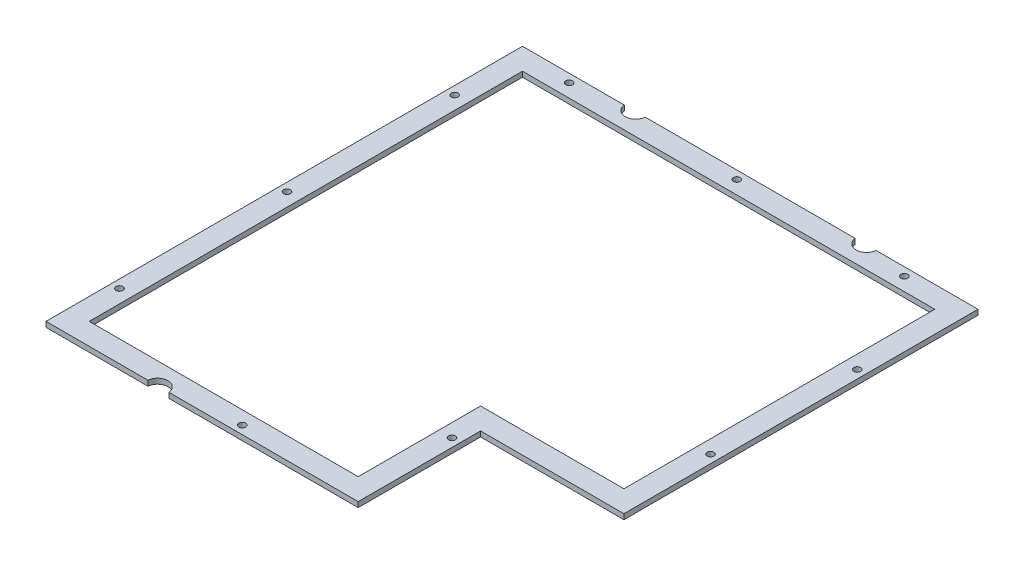
SolidWorks part; units mm, degrees
ref_plane "Front Plane" through (0, 0, 0) normal (0, 0, 1) x (1, 0, 0)
ref_plane "Top Plane" through (0, 0, 0) normal (0, 1, 0) x (1, 0, 0)
ref_plane "Right Plane" through (0, 0, 0) normal (1, 0, 0) x (0, 0, -1)
ref_plane "Plane1" through (0, 0, 0) normal (0, 1, 0) x (1, 0, 0)
sketch "Sketch1" plane through (0, 0, 0) normal (0, 1, 0) x (1, 0, 0)
  line L0 (-138.1125, 144.4625) -> (138.1125, 144.4625)
  line L1 (138.1125, 144.4625) -> (138.1125, -70.2437)
  line L2 (138.1125, -70.2437) -> (51.1937, -70.2437)
  line L3 (51.1937, -70.2437) -> (51.1937, -144.4625)
  line L4 (51.1937, -144.4625) -> (-138.1125, -144.4625)
  line L5 (-138.1125, -144.4625) -> (-138.1125, 144.4625)
  line L6 (-125.0188, 131.3688) -> (125.0188, 131.3688)
  line L7 (125.0188, 131.3688) -> (125.0188, -57.15)
  line L8 (125.0188, -57.15) -> (38.1, -57.15)
  line L9 (38.1, -57.15) -> (38.1, -131.3688)
  line L10 (38.1, -131.3688) -> (-125.0188, -131.3688)
  line L11 (-125.0188, -131.3688) -> (-125.0188, 131.3688)
  line L12 (0, -158.9087) -> (0, 158.9087) construction
  dimension "D1" = 13.0937
  dimension "D2" = 13.0937
  dimension "D3" = 13.0937
  dimension "D4" = 13.0937
  dimension "D5" = 13.0937
  dimension "D6" = 250.0376
  dimension "D7" = 262.7376
  dimension "D8" = 163.1188
  dimension "D9" = 188.5188
extrude "Extrude1" add sketch "Sketch1" along normal blind 3.175
sketch "Sketch2" plane through (0, 3.175, 0) normal (0, 1, 0) x (-1, 0, 0)
  line L0 (0, -158.9087) -> (0, 158.9087) construction
  circle A0 centre (24.13, 139.446) radius 2.0701
  circle A1 centre (104.775, -139.446) radius 2.0701
  circle A2 centre (3.175, -139.446) radius 2.0701
  circle A3 centre (133.096, 104.9366) radius 2.0701
  circle A4 centre (133.096, 3.3366) radius 2.0701
  circle A5 centre (133.096, -98.2634) radius 2.0701
  circle A6 centre (-98.425, -139.446) radius 2.0701
  circle A7 centre (-133.096, -76.2) radius 2.0701
  circle A8 centre (-133.096, 12.7) radius 2.0701
  circle A9 centre (-46.1772, 82.55) radius 2.0701
  point P20 (138.1125, 0)
  point P21 (-138.1125, 0)
  point P22 (0, 144.4625)
  point P23 (0, -144.4625)
extrude "Extrude2" cut sketch "Sketch2" against normal through all
sketch "Sketch3" plane through (0, 3.175, 0) normal (0, 1, 0) x (-1, 0, 0)
  circle A0 centre (69.9999, 145.001) radius 6.35
  circle A1 centre (69.9999, -145.001) radius 6.35
  circle A2 centre (-69.9999, -145.001) radius 6.35
extrude "Extrude3" cut sketch "Sketch3" against normal through all
